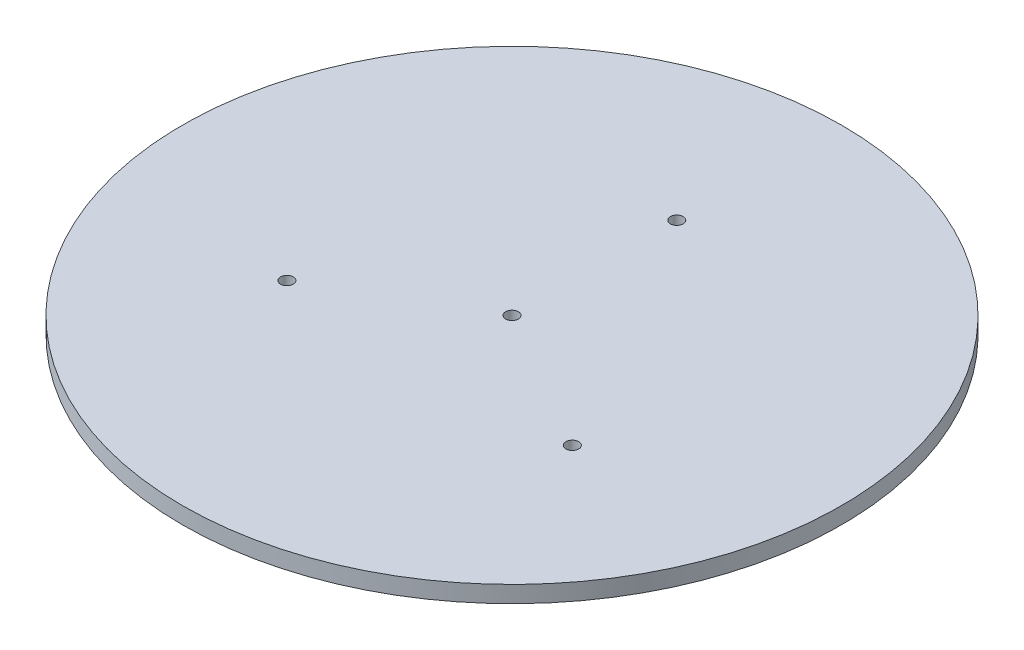
SolidWorks part; units mm, degrees
ref_plane "Front Plane" through (0, 0, 0) normal (0, 0, 1) x (1, 0, 0)
ref_plane "Top Plane" through (0, 0, 0) normal (0, 1, 0) x (1, 0, 0)
ref_plane "Right Plane" through (0, 0, 0) normal (1, 0, 0) x (0, 0, -1)
sketch "Sketch1" plane through (0, 0, 0) normal (0, 1, 0) x (1, 0, 0)
  line L0 (0, 0) -> (0, 125.3808) construction
  circle A0 centre (0, 0) radius 125.3808
  circle A1 centre (0, 62.6904) radius 2.4257
  circle A2 centre (54.2915, -31.3452) radius 2.4257
  circle A3 centre (-54.2915, -31.3452) radius 2.4257
  circle A4 centre (0, 0) radius 2.4257
  point P13 (0, 0)
  dimension "D1" = 250.7615
  dimension "D2" = 4.8514
  dimension "D4" = 4.8514
  dimension "D3" = 3
extrude "Boss-Extrude1" add sketch "Sketch1" along normal blind 6.35
